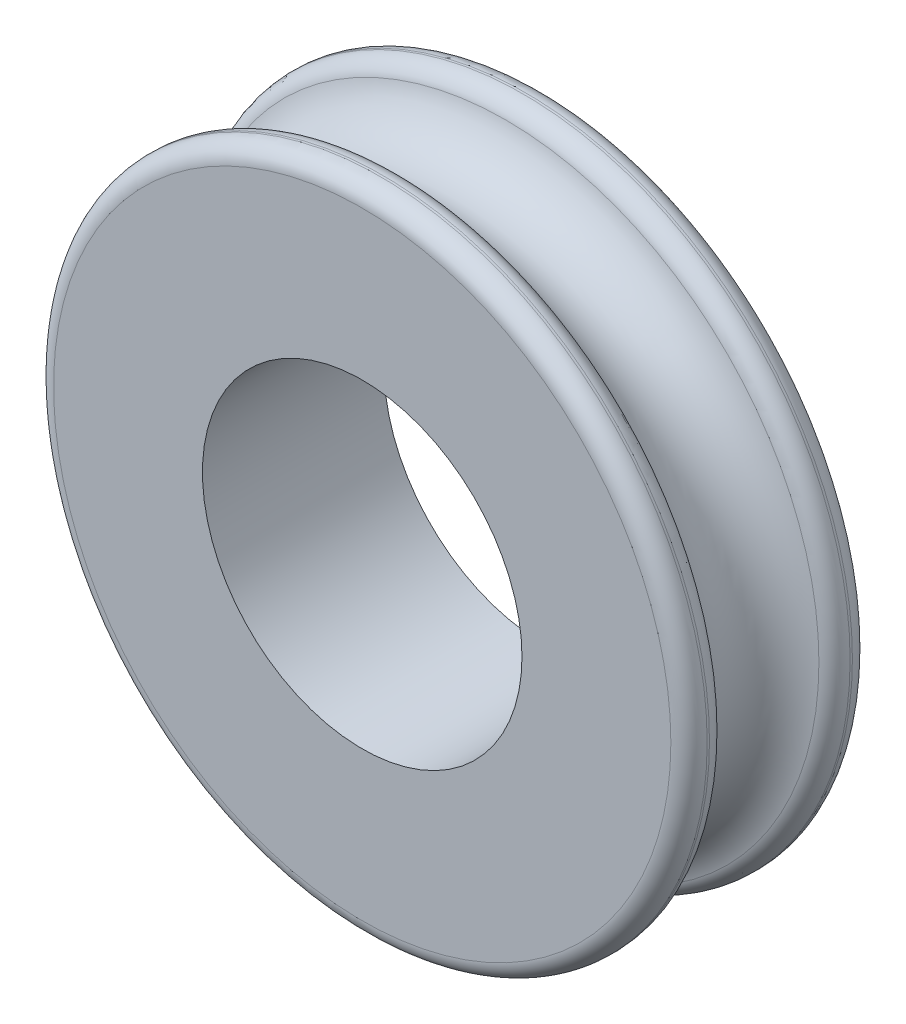
SolidWorks part; units mm, degrees
ref_plane "Front Plane" through (0, 0, 0) normal (0, 0, 1) x (1, 0, 0)
ref_plane "Top Plane" through (0, 0, 0) normal (0, 1, 0) x (1, 0, 0)
ref_plane "Right Plane" through (0, 0, 0) normal (1, 0, 0) x (0, 0, -1)
sketch "Эскиз1" plane through (0, 0, 0) normal (0, 0, 1) x (1, 0, 0)
  circle A0 centre (0, 0) radius 4.4
  circle A1 centre (0, 0) radius 9
  dimension "D1" = 8.8
  dimension "D2" = 18
extrude "Бобышка-Вытянуть1" add sketch "Эскиз1" along normal mid plane 5
sketch "Эскиз3" plane through (0, 0, 0) normal (0, 1, 0) x (1, 0, 0)
  line L0 (-13.6733, 0) -> (12.4977, 0) construction
  line L2 (9, -2.5) -> (9, 2.5) construction
  circle A0 centre (9, 0) radius 1.5
  point P5 (9, 0)
  dimension "D1" = 3
sketch "Эскиз4" plane through (0, 0, 0) normal (0, 0, 1) x (1, 0, 0)
  circle A0 centre (0, 0) radius 9 construction
  circle A1 centre (0, 0) radius 9
sweep "Вырез-По траектории1" cut profiles "Эскиз3" path "Эскиз4"
fillet "Скругление1" radius 0.5 2 edges at (9, 0, 2.5) (9, 0, -2.5)
fillet "Скругление2" radius 0.5 2 edges at (-9, 0, 1.5) (9, 0, -1.5)
